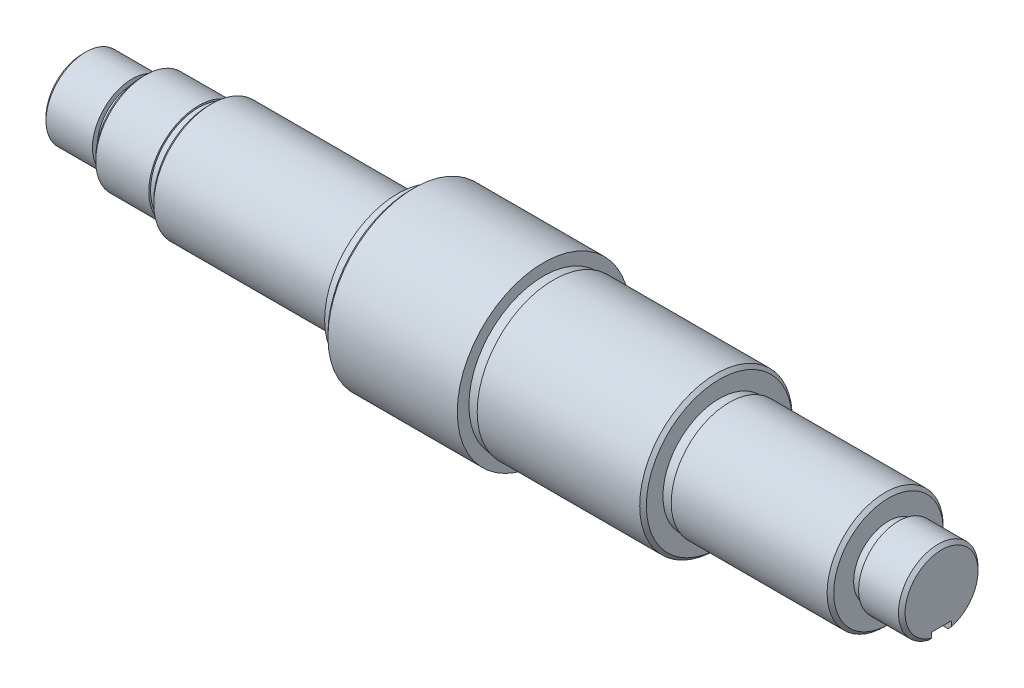
SolidWorks part; units mm, degrees
ref_plane "前视基准面" through (0, 0, 0) normal (0, 0, 1) x (1, 0, 0)
ref_plane "上视基准面" through (0, 0, 0) normal (0, 1, 0) x (1, 0, 0)
ref_plane "右视基准面" through (0, 0, 0) normal (1, 0, 0) x (0, 0, -1)
sketch "草图1" plane through (0, 0, 0) normal (0, 1, 0) x (1, 0, 0)
  line L0 (-109.712, 119.0721) -> (96.5817, 119.0721) construction
  line L1 (-86.2785, 104.0721) -> (-86.2785, 108.5721)
  line L6 (-104.2785, 119.0721) -> (-89.2785, 119.0721)
  line L7 (-104.2785, 119.0721) -> (-104.2785, 107.0721)
  line L8 (-104.2785, 107.0721) -> (-89.2785, 107.0721)
  line L9 (-89.2785, 119.0721) -> (-89.2785, 107.0721)
  line L10 (-89.2785, 108.5721) -> (-86.2785, 108.5721)
  line L11 (-89.2785, 108.5721) -> (-89.2785, 119.0721)
  line L12 (-89.2785, 119.0721) -> (-86.2785, 119.0721)
  line L13 (-86.2785, 108.5721) -> (-86.2785, 119.0721)
  line L14 (-86.2785, 119.0721) -> (-69.2785, 119.0721)
  line L15 (-86.2785, 119.0721) -> (-86.2785, 104.0721)
  line L16 (-86.2785, 104.0721) -> (-69.2785, 104.0721)
  line L17 (-69.2785, 119.0721) -> (-69.2785, 104.0721)
  line L18 (-69.2785, 119.0721) -> (-66.2785, 119.0721)
  line L19 (-69.2785, 119.0721) -> (-69.2785, 104.5721)
  line L20 (-69.2785, 104.5721) -> (-66.2785, 104.5721)
  line L21 (-66.2785, 119.0721) -> (-66.2785, 104.5721)
  line L22 (-66.2785, 119.0721) -> (-12.2785, 119.0721)
  line L23 (-66.2785, 119.0721) -> (-66.2785, 101.5721)
  line L24 (-66.2785, 101.5721) -> (-12.2785, 101.5721)
  line L25 (-12.2785, 119.0721) -> (-12.2785, 101.5721)
  line L26 (-12.2785, 119.0721) -> (-9.2785, 119.0721)
  line L27 (-12.2785, 119.0721) -> (-12.2785, 102.0721)
  line L28 (-12.2785, 102.0721) -> (-9.2785, 102.0721)
  line L29 (-9.2785, 119.0721) -> (-9.2785, 102.0721)
  line L30 (-9.2785, 119.0721) -> (-5.2785, 119.0721)
  line L31 (-9.2785, 119.0721) -> (-9.2785, 97.0721)
  line L32 (-9.2785, 97.0721) -> (-5.2785, 97.0721)
  line L33 (-5.2785, 119.0721) -> (-5.2785, 97.0721)
  line L34 (-5.2785, 119.0721) -> (34.7215, 119.0721)
  line L35 (-5.2785, 119.0721) -> (-5.2785, 93.0721)
  line L36 (-5.2785, 93.0721) -> (34.7215, 93.0721)
  line L37 (34.7215, 119.0721) -> (34.7215, 93.0721)
  line L38 (34.7215, 119.0721) -> (37.7215, 119.0721)
  line L39 (34.7215, 119.0721) -> (34.7215, 96.5721)
  line L40 (34.7215, 96.5721) -> (37.7215, 96.5721)
  line L41 (37.7215, 119.0721) -> (37.7215, 96.5721)
  line L42 (37.7215, 119.0721) -> (87.7215, 119.0721)
  line L43 (37.7215, 119.0721) -> (37.7215, 96.0721)
  line L44 (37.7215, 96.0721) -> (87.7215, 96.0721)
  line L45 (87.7215, 119.0721) -> (87.7215, 96.0721)
  line L46 (87.7215, 119.0721) -> (90.7215, 119.0721)
  line L47 (87.7215, 119.0721) -> (87.7215, 102.0721)
  line L48 (87.7215, 102.0721) -> (90.7215, 102.0721)
  line L49 (90.7215, 119.0721) -> (90.7215, 102.0721)
  line L50 (90.7215, 119.0721) -> (138.7215, 119.0721)
  line L51 (90.7215, 119.0721) -> (90.7215, 101.5721)
  line L52 (90.7215, 101.5721) -> (138.7215, 101.5721)
  line L53 (138.7215, 119.0721) -> (138.7215, 101.5721)
  line L54 (138.7215, 119.0721) -> (154.7215, 119.0721)
  line L55 (138.7215, 119.0721) -> (138.7215, 107.0721)
  line L56 (141.7215, 107.0721) -> (154.7215, 107.0721)
  line L57 (154.7215, 119.0721) -> (154.7215, 107.0721)
  line L58 (138.7215, 108.5721) -> (141.7215, 108.5721)
  line L59 (154.7215, 119.0721) -> (170.8968, 119.0721)
  line L60 (154.7215, 119.0721) -> (154.7215, 105.8866)
  line L63 (138.7215, 119.0721) -> (141.7215, 119.0721)
  line L64 (138.7215, 119.0721) -> (138.7215, 104.2577)
  line L66 (141.7215, 119.0721) -> (141.7215, 107.0721)
  point P42 (-104.2785, 113.0721)
  point P43 (154.7215, 113.0721)
  dimension "D2" = 18
  dimension "D3" = 3
  dimension "D4" = 1.5
  dimension "D5" = 38
  dimension "D6" = 15
  dimension "D7" = 12
  dimension "D8" = 3
  dimension "D9" = 0.5
  dimension "D10" = 95
  dimension "D11" = 3
  dimension "D12" = 0.5
  dimension "D13" = 17.5
  dimension "D14" = 4
  dimension "D15" = 22
  dimension "D16" = 26
  dimension "D17" = 259
  dimension "D18" = 3
  dimension "D19" = 0.5
  dimension "D20" = 3
  dimension "D21" = 17.5
  dimension "D22" = 23
  dimension "D23" = 3
  dimension "D24" = 0.5
  dimension "D25" = 16
  dimension "D26" = 1.5
  dimension "D27" = 120
  dimension "D28" = 67
  dimension "D29" = 12
revolve "旋转1" add sketch "草图1" angle 360 about L0
cosmetic thread "装饰螺纹线1" parameters "D2"=23
cosmetic thread "装饰螺纹线2" parameters "D2"=23
chamfer "倒角1" distance 1 angle 45 7 edges at (-104.2785, 0, -107.0721) (154.7215, 0, -107.0721) (138.7215, 0, -101.5721) (87.7215, 0, -96.0721) (-5.2785, 0, -93.0721) (-66.2785, 0, -101.5721) (-86.2785, 0, -104.0721)
ref_plane "基准面1" through (0, -15, 0) normal (0, -1, 0) x (-1, 0, 0)
sketch "草图2" plane through (0, -15, 0) normal (0, -1, 0) x (-1, 0, 0)
  line L0 (85.2785, 119.0721) -> (69.2785, 119.0721) construction
  line L1 (85.2785, 134.0721) -> (85.2785, 104.0721) construction
  line L2 (69.2785, 133.5721) -> (69.2785, 104.5721) construction
  line L3 (78.2785, 119.0721) -> (76.2785, 119.0721) construction
  line L7 (77.2785, 134.0721) -> (77.2785, 109.7699) construction
  line L8 (85.2785, 134.0721) -> (69.2785, 134.0721) construction
  line L9 (78.2785, 115.0721) -> (76.2785, 115.0721)
  line L10 (78.2785, 123.0721) -> (76.2785, 123.0721)
  arc A2 (78.2785, 115.0721) -> (78.2785, 123.0721) centre (78.2785, 119.0721) ccw
  arc A3 (76.2785, 123.0721) -> (76.2785, 115.0721) centre (76.2785, 119.0721) ccw
  point P8 (77.2785, 119.0721)
  dimension "D2" = 10
  dimension "D1" = 8
extrude "切除-拉伸1" cut sketch "草图2" against normal blind 4
ref_plane "基准面2" through (0, -23, 0) normal (0, -1, 0) x (-1, 0, 0)
sketch "草图3" plane through (0, -23, 0) normal (0, -1, 0) x (-1, 0, 0)
  line L0 (-62.2215, 96.0721) -> (-62.2215, 142.0721) construction
  line L1 (-86.7215, 96.0721) -> (-37.7215, 96.0721) construction
  line L2 (-37.7215, 142.0721) -> (-86.7215, 142.0721) construction
  line L3 (-62.2215, 119.0721) -> (-83.2215, 119.0721) construction
  line L4 (-48.7215, 119.0721) -> (-72.7215, 119.0721) construction
  line L11 (-48.7215, 113.0721) -> (-72.7215, 113.0721)
  line L12 (-48.7215, 125.0721) -> (-72.7215, 125.0721)
  line L16 (-37.7215, 96.5721) -> (-37.7215, 141.5721) construction
  arc A2 (-48.7215, 113.0721) -> (-48.7215, 125.0721) centre (-48.7215, 119.0721) ccw
  arc A3 (-72.7215, 125.0721) -> (-72.7215, 113.0721) centre (-72.7215, 119.0721) ccw
  point P7 (-60.7215, 119.0721)
  dimension "D1" = 5
  dimension "D2" = 12
  dimension "D3" = 24
extrude "切除-拉伸2" cut sketch "草图3" against normal blind 5
ref_plane "基准面3" through (0, -12, 0) normal (0, -1, 0) x (-1, 0, 0)
sketch "草图5" plane through (0, -12, 0) normal (0, -1, 0) x (-1, 0, 0)
  line L0 (-153.7215, 119.0721) -> (-141.7215, 119.0721) construction
  line L1 (-153.7215, 107.0721) -> (-153.7215, 131.0721) construction
  line L2 (-141.7215, 107.0721) -> (-141.7215, 131.0721) construction
  line L3 (-147.7215, 119.0721) -> (-147.7215, 127.9529) construction
  line L9 (-154.729, 122.0721) -> (-138.729, 122.0721)
  line L10 (-154.729, 122.0721) -> (-154.729, 116.0721)
  line L11 (-154.729, 116.0721) -> (-138.729, 116.0721)
  line L12 (-138.729, 122.0721) -> (-138.729, 116.0721)
  dimension "D1" = 16
  dimension "D2" = 3
extrude "切除-拉伸3" cut sketch "草图5" against normal blind 3
